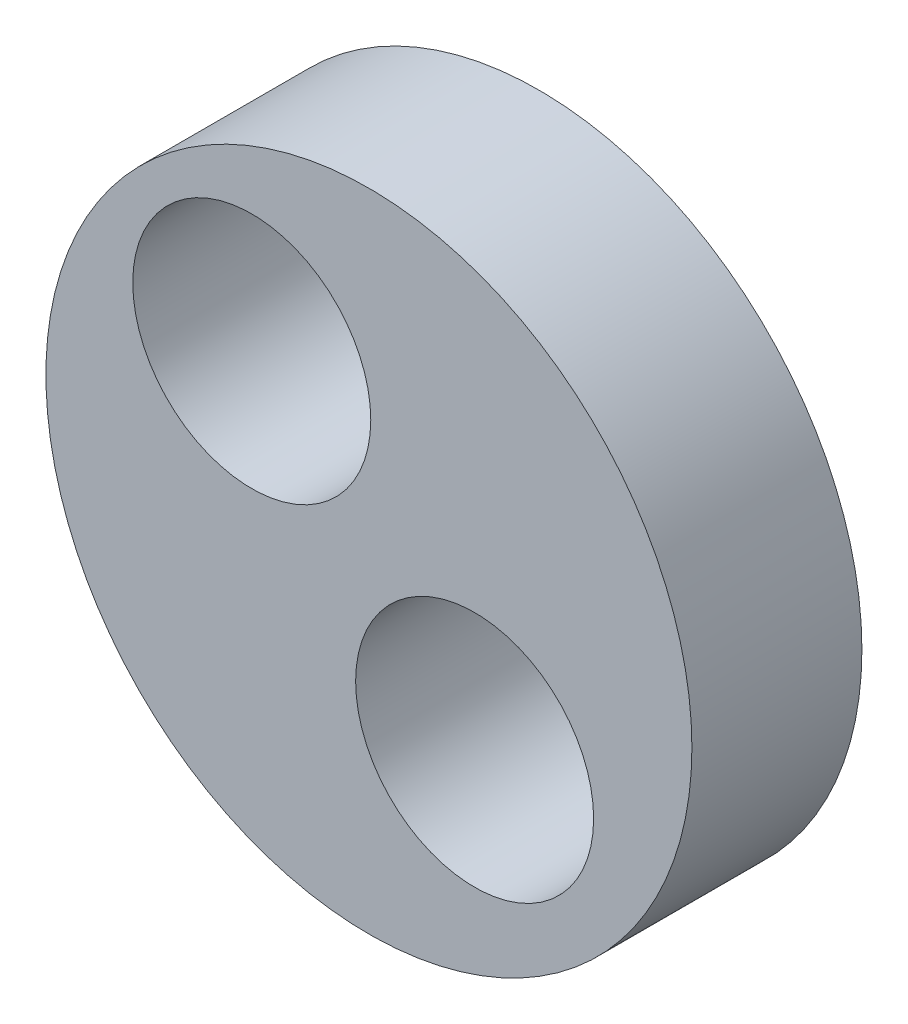
SolidWorks part; units mm, degrees
ref_plane "Front Plane" through (0, 0, 0) normal (0, 0, 1) x (1, 0, 0)
ref_plane "Top Plane" through (0, 0, 0) normal (0, 1, 0) x (1, 0, 0)
ref_plane "Right Plane" through (0, 0, 0) normal (1, 0, 0) x (0, 0, -1)
sketch "Sketch1" plane through (0, 0, 0) normal (0, 0, 1) x (1, 0, 0)
  circle A0 centre (0, 0) radius 12.065
  dimension "D1" = 24.13
extrude "Extrude1" add sketch "Sketch1" along normal blind 6.35
sketch "Sketch2" plane through (0, 0, 0) normal (0, 0, -1) x (-1, 0, 0)
  circle A0 centre (4.3755, 4.6019) radius 4.445
  dimension "D1" = 8.89
  dimension "D2" = 6.35
extrude "Cut-Extrude1" cut sketch "Sketch2" against normal blind 25.4
sketch "Sketch3" plane through (0, 0, 0) normal (0, 0, -1) x (-1, 0, 0)
  circle A0 centre (-3.9492, -4.131) radius 4.445
  dimension "D2" = 8.89
  dimension "D1" = 5.715
extrude "Cut-Extrude2" cut sketch "Sketch3" against normal blind 25.4
